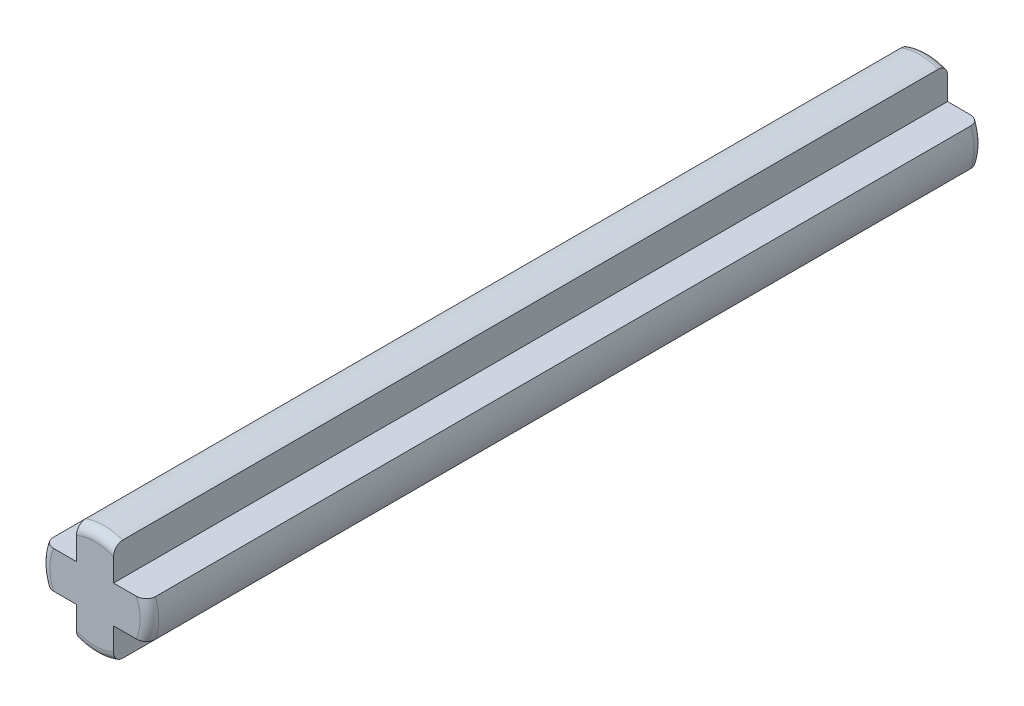
SolidWorks part; units mm, degrees
ref_plane "Front Plane" through (0, 0, 0) normal (0, 0, 1) x (1, 0, 0)
ref_plane "Top Plane" through (0, 0, 0) normal (0, 1, 0) x (1, 0, 0)
ref_plane "Right Plane" through (0, 0, 0) normal (1, 0, 0) x (0, 0, -1)
sketch "Croquis1" plane through (0, 0, 0) normal (0, 0, 1) x (1, 0, 0)
  line L0 (0.8, 2.2096) -> (0.8, 0.8)
  line L1 (-0.8, -2.2096) -> (-0.8, -0.8)
  line L2 (-2.2096, 0.8) -> (-0.8, 0.8)
  line L3 (2.2096, -0.8) -> (0.8, -0.8)
  line L4 (-0.8, 0.8) -> (-0.8, 2.2096)
  line L5 (0.8, 0.8) -> (2.2096, 0.8)
  line L6 (0.8, -0.8) -> (0.8, -2.2096)
  line L7 (-0.8, -0.8) -> (-2.2096, -0.8)
  arc A1 (-2.2096, 0.8) -> (-2.2096, -0.8) centre (0, 0) ccw
  arc A2 (0.8, 2.2096) -> (-0.8, 2.2096) centre (0, 0) ccw
  arc A3 (2.2096, -0.8) -> (2.2096, 0.8) centre (0, 0) ccw
  arc A4 (-0.8, -2.2096) -> (0.8, -2.2096) centre (0, 0) ccw
  point P14 (0, 0)
  dimension "D2" = 4.7
  dimension "D3" = 0.8
  dimension "D4" = 1.6
  dimension "D5" = 0.8
  dimension "D6" = 1.6
extrude "Saliente-Extruir1" add sketch "Croquis1" along normal blind 36
fillet "Redondeo2" radius 0.4 8 edges at (0, -2.35, 0) (2.35, 0, 0) (-2.35, 0, 0) (0, 2.35, 0) (0, -2.35, 36) (2.35, 0, 36) (-2.35, 0, 36) (0, 2.35, 36)
